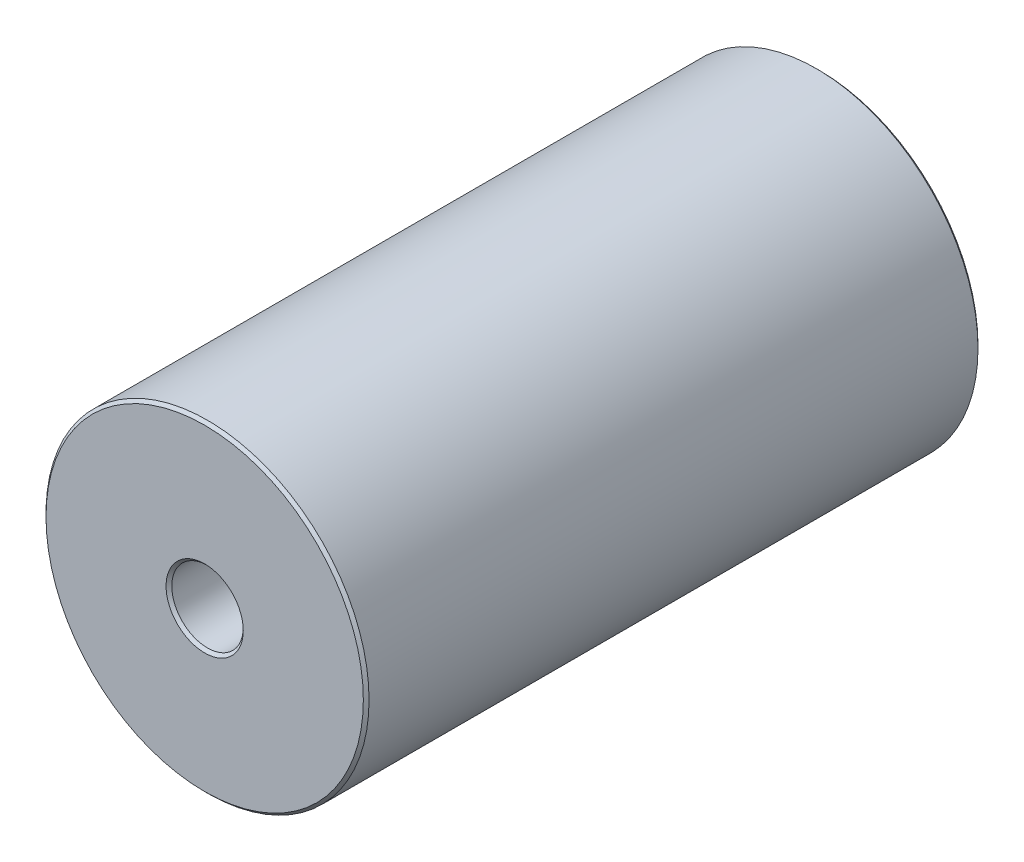
SolidWorks part; units mm, degrees
material "1060 Alloy"
ref_plane "Front Plane" through (0, 0, 0) normal (0, 0, 1) x (1, 0, 0)
ref_plane "Top Plane" through (0, 0, 0) normal (0, 1, 0) x (1, 0, 0)
ref_plane "Right Plane" through (0, 0, 0) normal (1, 0, 0) x (0, 0, -1)
sketch "Sketch1" plane through (0, 0, 0) normal (0, 0, 1) x (1, 0, 0)
  circle A0 centre (0, 0) radius 3.175
  circle A1 centre (0, 0) radius 14.351
  dimension "D1" = 6.35
  dimension "D2" = 28.702
extrude "Boss-Extrude1" add sketch "Sketch1" along normal blind 54.61
chamfer "Chamfer1" distance 0.254 angle 45 4 edges at (3.175, 0, 0) (14.351, 0, 0) (3.175, 0, 54.61) (14.351, 0, 54.61)
